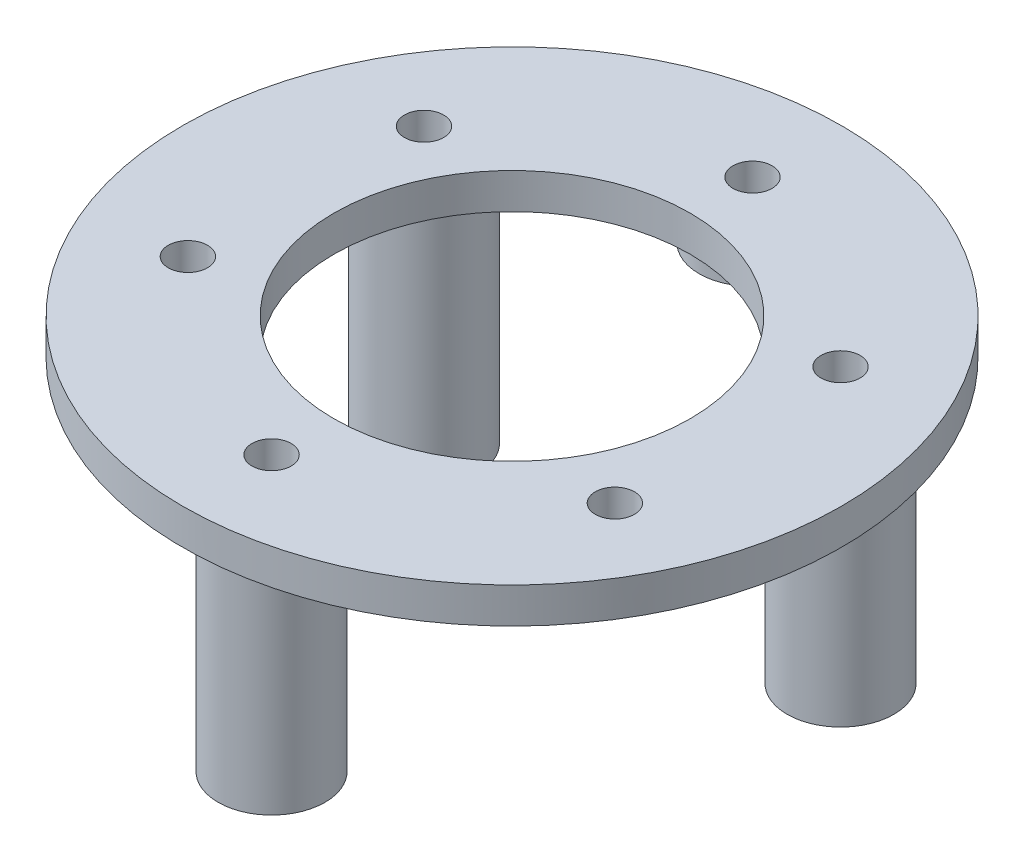
SolidWorks part; units mm, degrees
ref_plane "Спереди" through (0, 0, 0) normal (0, 0, 1) x (1, 0, 0)
ref_plane "Сверху" through (0, 0, 0) normal (0, 1, 0) x (1, 0, 0)
ref_plane "Справа" through (0, 0, 0) normal (1, 0, 0) x (0, 0, -1)
sketch "Эскиз1" plane through (0, 0, 0) normal (0, 1, 0) x (1, 0, 0)
  line L0 (0, 0) -> (0, 13.5) construction
  line L1 (0, 0) -> (-11.9855, -6.2127) construction
  line L2 (0, 0) -> (11.9855, -6.2127) construction
  circle A0 centre (0, 0) radius 10
  circle A1 centre (0, 0) radius 18.5
  circle A2 centre (0, 13.5) radius 1.1
  circle A3 centre (11.9855, -6.2127) radius 1.1
  circle A4 centre (-11.9855, -6.2127) radius 1.1
  dimension "D1" = 20
  dimension "D2" = 37
  dimension "D3" = 2.2
  dimension "D4" = 117.4
  dimension "D5" = 117.4
  dimension "D6" = 13.5
extrude "Бобышка-Вытянуть1" add sketch "Эскиз1" along normal blind 2
sketch "Эскиз2" plane through (0, 2, 0) normal (0, 1, 0) x (1, 0, 0)
  circle A0 centre (0, 13.5) radius 1.1
  circle A1 centre (0, 13.5) radius 3
  circle A2 centre (-11.9855, -6.2127) radius 1.1
  circle A3 centre (-11.9855, -6.2127) radius 3
  circle A4 centre (11.9855, -6.2127) radius 1.1
  circle A5 centre (11.9855, -6.2127) radius 3
  dimension "D1" = 6
  dimension "D2" = 2.2
extrude "Бобышка-Вытянуть2" add sketch "Эскиз2" against normal blind 1.2 from surface at -2 starting at face at (0, 0, 18.5)
sketch "Эскиз3" plane through (0, 2, 0) normal (0, 1, 0) x (1, 0, 0)
  line L0 (0, 0) -> (0, 19.3962) construction
  line L1 (0, 0) -> (-11.6913, 6.75) construction
  line L2 (0, 0) -> (0, -13.5) construction
  line L3 (0, 0) -> (11.6913, 6.75) construction
  circle A0 centre (-11.6913, 6.75) radius 1.1
  circle A1 centre (11.6913, 6.75) radius 1.1
  circle A2 centre (0, -13.5) radius 1.1
  dimension "D2" = 2.2
  dimension "D1" = 13.5
  dimension "D3" = 120
  dimension "D4" = 120
extrude "Вырез-Вытянуть1" cut sketch "Эскиз3" against normal through all
sketch "Эскиз4" plane through (0, 0, 0) normal (0, -1, 0) x (1, 0, 0)
  circle A0 centre (-11.6913, -6.75) radius 1.1
  circle A1 centre (-11.6913, -6.75) radius 3
  circle A2 centre (0, 13.5) radius 1.1
  circle A3 centre (0, 13.5) radius 3
  circle A4 centre (11.6913, -6.75) radius 1.1
  circle A5 centre (11.6913, -6.75) radius 3
  dimension "D1" = 2.2
  dimension "D2" = 6
extrude "Бобышка-Вытянуть3" add sketch "Эскиз4" along normal blind 13.4
sketch "Эскиз5" plane through (0, 0, 0) normal (0, -1, 0) x (1, 0, 0)
  line L0 (0, 0) -> (-9.6213, -16.6646) construction
  line L1 (0, 0) -> (0, -24.9549) construction
  line L3 (-8.384, -16.5215) -> (-6.384, -13.0574)
  line L4 (-8.384, -16.5215) -> (-10.116, -15.5215)
  line L5 (-10.116, -15.5215) -> (-8.116, -12.0574)
  line L6 (-6.384, -13.0574) -> (-8.116, -12.0574)
  line L7 (-8.384, -16.5215) -> (-8.116, -12.0574) construction
  line L8 (-10.116, -15.5215) -> (-6.384, -13.0574) construction
  point P3 (-8.25, -14.2894)
  dimension "D1" = 30
  dimension "D2" = 2
  dimension "D3" = 4
  dimension "D4" = 16.5
extrude "Вырез-Вытянуть2" cut sketch "Эскиз5" against normal blind 0.44
